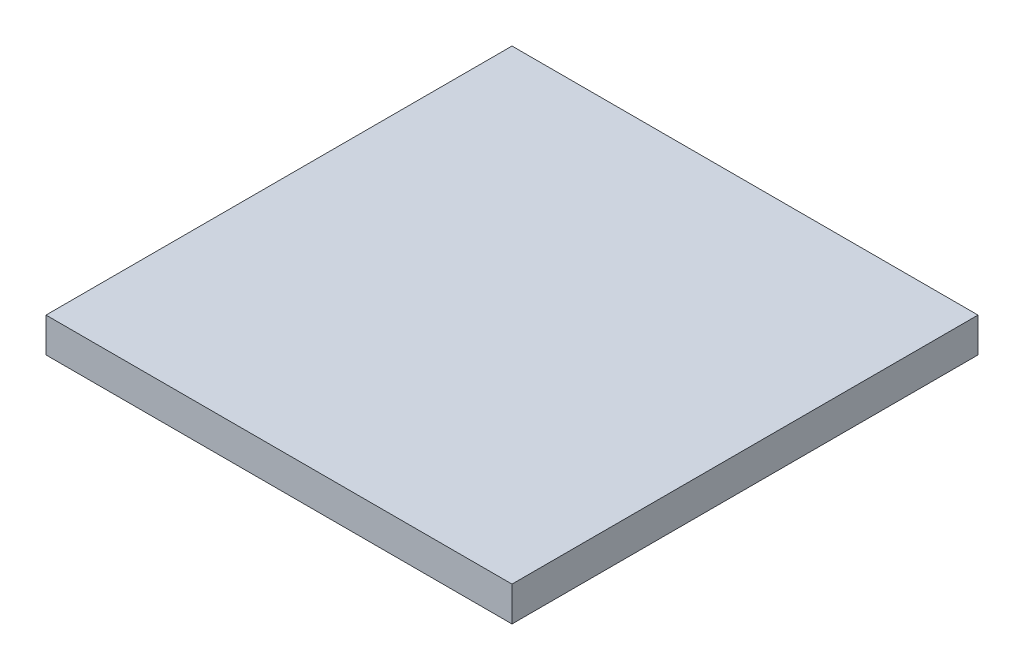
SolidWorks part; units mm, degrees
ref_plane "Front Plane" through (0, 0, 0) normal (0, 0, 1) x (1, 0, 0)
ref_plane "Top Plane" through (0, 0, 0) normal (0, 1, 0) x (1, 0, 0)
ref_plane "Right Plane" through (0, 0, 0) normal (1, 0, 0) x (0, 0, -1)
sketch "Sketch1" plane through (0, 0, 0) normal (0, 1, 0) x (1, 0, 0)
  line L1 (9.575, -9.575) -> (-9.575, -9.575)
  line L2 (9.575, -9.575) -> (9.575, 9.575)
  line L3 (9.575, 9.575) -> (-9.575, 9.575)
  line L4 (-9.575, -9.575) -> (-9.575, 9.575)
  line L5 (9.575, -9.575) -> (-9.575, 9.575) construction
  line L6 (9.575, 9.575) -> (-9.575, -9.575) construction
  point P0 (0, 0)
  dimension "D1" = 19.15
  dimension "D2" = 19.15
extrude "Boss-Extrude1" add sketch "Sketch1" along normal blind 1.42
sketch "Sketch2" plane through (0, 0, 0) normal (0, -1, 0) x (1, 0, 0)
  line L0 (-8.775, -8.57) -> (-8.775, -8.98)
  line L1 (8.775, 8.775) -> (-8.775, 8.775) construction
  line L2 (8.775, 8.775) -> (8.775, -8.775) construction
  line L3 (8.775, -8.775) -> (-8.775, -8.775) construction
  line L4 (-8.775, 8.775) -> (-8.775, -8.775) construction
  line L5 (8.775, 8.775) -> (-8.775, -8.775) construction
  line L6 (8.775, -8.775) -> (-8.775, 8.775) construction
  arc A0 (-8.775, -8.98) -> (-8.775, -8.57) centre (-8.775, -8.775) ccw
  point P0 (0, 0)
  dimension "D3" = 0.41
  dimension "D1" = 17.55
  dimension "D2" = 17.55
equation "\"D2@Sketch2\"=\"D1@Sketch2\""
